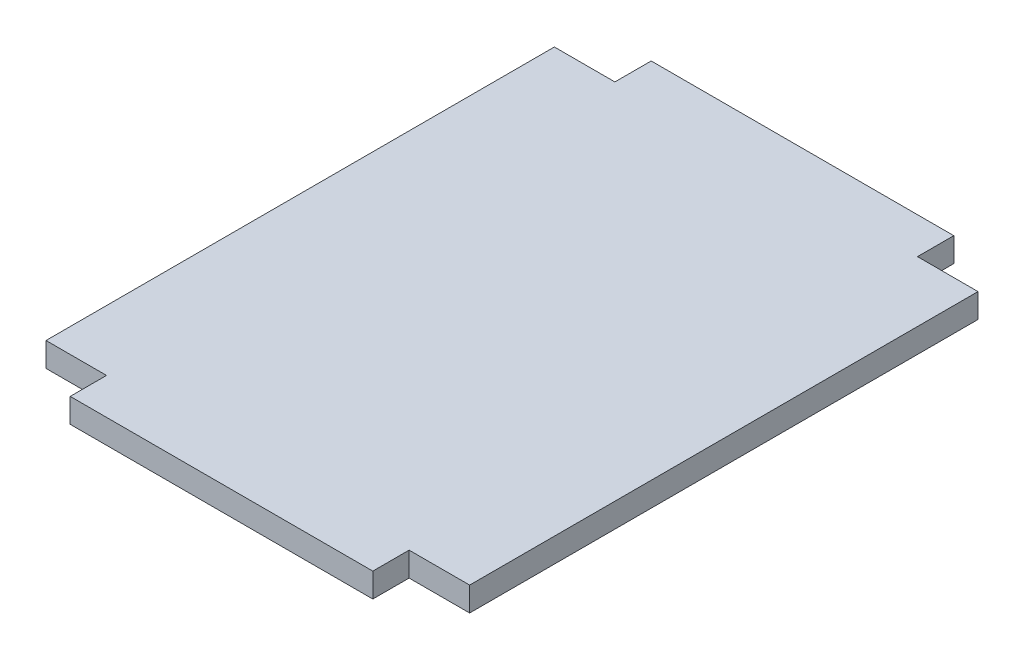
SolidWorks part; units mm, degrees
material "PVC rigido"
ref_plane "Piano frontale" through (0, 0, 0) normal (0, 0, 1) x (1, 0, 0)
ref_plane "Piano superiore" through (0, 0, 0) normal (0, 1, 0) x (1, 0, 0)
ref_plane "Piano destro" through (0, 0, 0) normal (1, 0, 0) x (0, 0, -1)
sketch "Schizzo1" plane through (0, 0, 0) normal (0, 0, 1) x (1, 0, 0)
  line L1 (48, -53.5) -> (23, -53.5)
  line L2 (48, -53.5) -> (48, -55.5)
  line L3 (48, -55.5) -> (23, -55.5)
  line L4 (23, -53.5) -> (23, -55.5)
extrude "Estrusione-Estrusione1" add sketch "Schizzo1" along normal up to surface (45 mm away) and the other way up to surface (3 mm away)
ref_plane "Piano1" through (35.5, 0, 0) normal (1, 0, 0) x (0, 0, -1)
sketch "Schizzo2" plane through (48, 0, 0) normal (1, 0, 0) x (0, 0, -1)
  line L0 (-45, -55.5) -> (3, -55.5) construction
  line L1 (0, -53.5) -> (-42, -53.5)
  line L2 (0, -53.5) -> (0, -55.5)
  line L3 (0, -55.5) -> (-42, -55.5)
  line L4 (-42, -53.5) -> (-42, -55.5)
  line L5 (-42, -55.5) -> (-42, -53.5) construction
extrude "Estrusione-Estrusione2" add sketch "Schizzo2" along normal blind 5
mirror "Specchia1" about plane through (35.5, 0, 0) normal (1, 0, 0) of "Estrusione-Estrusione2"
